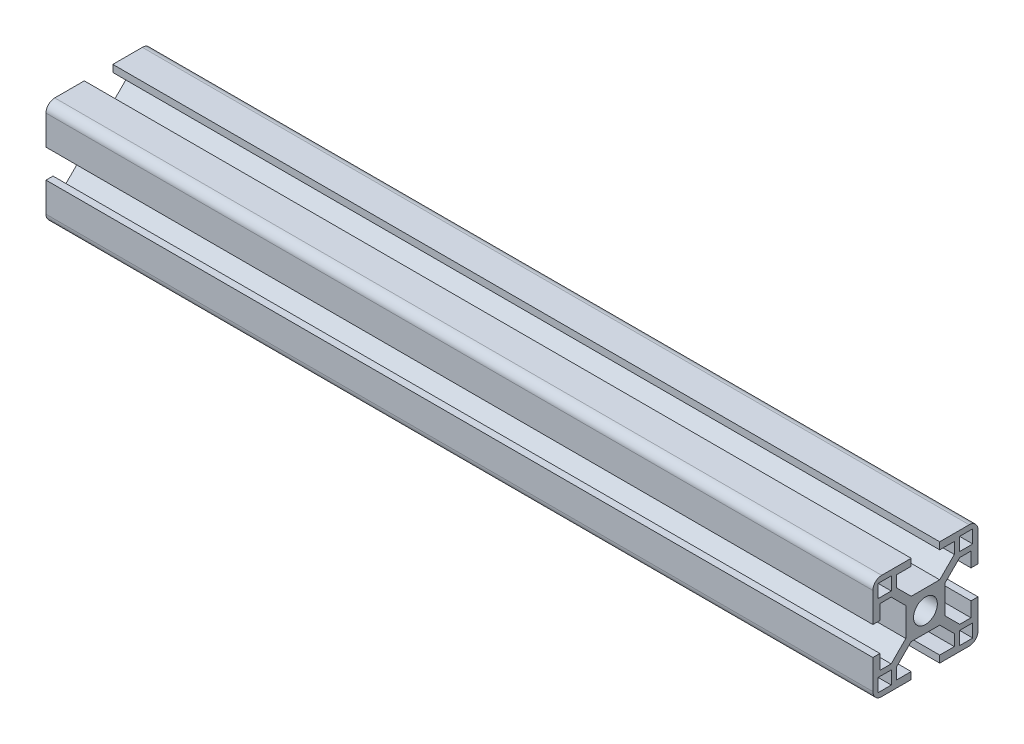
SolidWorks part; units mm, degrees
material "6061 Alloy"
material "6061 Alloy"
ref_plane "Front Plane" through (0, 0, 0) normal (0, 0, 1) x (1, 0, 0)
ref_plane "Top Plane" through (0, 0, 0) normal (0, 1, 0) x (1, 0, 0)
ref_plane "Right Plane" through (0, 0, 0) normal (1, 0, 0) x (0, 0, -1)
sketch "Sketch1" plane through (0, 0, 0) normal (0, 0, 1) x (1, 0, 0)
  line L0 (0, 0) -> (236, 0)
  dimension "D1" = 236
other "T-slot profiles 3030_2(1)"
ref_plane "Plane1" through (0, 0, 0) normal (1, 0, 0) x (0, 1, 0)
sketch "Sketch11" plane through (0, 0, 0) normal (1, 0, 0) x (0, 1, 0)
  line L0 (0, 15) -> (0, -15) construction
  line L1 (-15, -15) -> (15, -15) construction
  line L2 (-15, -15) -> (-15, 15) construction
  line L3 (-15, 15) -> (15, 15) construction
  line L4 (15, -15) -> (15, 15) construction
  line L5 (-15, -15) -> (15, 15) construction
  line L6 (-15, 15) -> (15, -15) construction
  line L7 (-4.07, 5.6) -> (4.07, 5.6)
  line L8 (0, 0) -> (15, 0) construction
  line L9 (-4.07, -5.6) -> (4.07, -5.6)
  line L10 (5.6, -4.07) -> (5.6, 4.07)
  line L11 (-5.6, -4.07) -> (-5.6, 4.07)
  line L12 (-4.07, 5.6) -> (-8.25, 9.78)
  line L13 (4.07, 5.6) -> (8.25, 9.78)
  line L14 (-8.25, 9.78) -> (8.25, 9.78) construction
  line L15 (8.25, 9.78) -> (8.25, 13)
  line L16 (8.25, 13) -> (4.07, 13)
  line L17 (4.07, 13) -> (4.07, 15)
  line L18 (4.07, 15) -> (12.5, 15)
  line L19 (15, 12.5) -> (15, 4.07)
  line L20 (9.78, 8.25) -> (13, 8.25)
  line L21 (13, 8.25) -> (13, 4.07)
  line L22 (9.78, 8.25) -> (5.6, 4.07)
  line L23 (8.25, 9.78) -> (9.78, 8.25) construction
  line L24 (13, 4.07) -> (15, 4.07)
  line L25 (5.6, -4.07) -> (9.78, -8.25)
  line L26 (9.75, 13.5) -> (13.5, 13.5)
  line L27 (9.75, 13.5) -> (9.75, 9.75)
  line L28 (9.75, 9.75) -> (13.5, 9.75)
  line L29 (13.5, 13.5) -> (13.5, 9.75)
  line L30 (9.75, 13.5) -> (13.5, 9.75) construction
  line L31 (9.75, 9.75) -> (13.5, 13.5) construction
  line L32 (9.78, -8.25) -> (13, -8.25)
  line L33 (13, -8.25) -> (13, -4.07)
  line L34 (13, -4.07) -> (15, -4.07)
  line L35 (15, -4.07) -> (15, -12.5)
  line L36 (4.07, -5.6) -> (8.25, -9.78)
  line L37 (8.25, -9.78) -> (8.25, -13)
  line L38 (8.25, -13) -> (4.07, -13)
  line L39 (4.07, -13) -> (4.07, -15)
  line L40 (4.07, -15) -> (12.5, -15)
  line L41 (-4.07, -5.6) -> (-8.25, -9.78)
  line L42 (-8.25, -9.78) -> (-8.25, -13)
  line L43 (-8.25, -13) -> (-4.07, -13)
  line L44 (-4.07, -13) -> (-4.07, -15)
  line L45 (-4.07, -15) -> (-12.5, -15)
  line L46 (-8.25, 9.78) -> (-8.25, 13)
  line L47 (-8.25, 13) -> (-4.07, 13)
  line L48 (-4.07, 13) -> (-4.07, 15)
  line L49 (-4.07, 15) -> (-12.5, 15)
  line L50 (-5.6, 4.07) -> (-9.78, 8.25)
  line L51 (-9.78, 8.25) -> (-13, 8.25)
  line L52 (-13, 8.25) -> (-13, 4.07)
  line L53 (-13, 4.07) -> (-15, 4.07)
  line L54 (-15, 4.07) -> (-15, 12.5)
  line L55 (-5.6, -4.07) -> (-9.78, -8.25)
  line L56 (-9.78, -8.25) -> (-13, -8.25)
  line L57 (-13, -8.25) -> (-13, -4.07)
  line L58 (-13, -4.07) -> (-15, -4.07)
  line L59 (-15, -4.07) -> (-15, -12.5)
  line L60 (9.75, -9.75) -> (13.5, -9.75)
  line L61 (13.5, -13.5) -> (13.5, -9.75)
  line L62 (9.75, -13.5) -> (13.5, -13.5)
  line L63 (9.75, -13.5) -> (9.75, -9.75)
  line L64 (-9.75, 9.75) -> (-13.5, 9.75)
  line L65 (-13.5, 13.5) -> (-13.5, 9.75)
  line L66 (-9.75, 13.5) -> (-13.5, 13.5)
  line L67 (-9.75, 13.5) -> (-9.75, 9.75)
  line L68 (-9.75, -13.5) -> (-9.75, -9.75)
  line L69 (-9.75, -13.5) -> (-13.5, -13.5)
  line L70 (-13.5, -13.5) -> (-13.5, -9.75)
  line L71 (-9.75, -9.75) -> (-13.5, -9.75)
  arc A0 (-15, 12.5) -> (-12.5, 15) centre (-12.5, 12.5) cw
  arc A1 (12.5, -15) -> (15, -12.5) centre (12.5, -12.5) ccw
  arc A2 (15, 12.5) -> (12.5, 15) centre (12.5, 12.5) ccw
  arc A3 (-12.5, -15) -> (-15, -12.5) centre (-12.5, -12.5) cw
  circle A4 centre (0, 0) radius 3.4
  point P0 (0, 0)
  point P6 (0, 0)
  point P7 (-12.5, 12.5)
  point P26 (0, 5.6)
  point P32 (5.6, 0)
  point P44 (11.625, 11.625)
  dimension "D4" = 6.8
  dimension "D3" = 2.5
  dimension "D1" = 30
  dimension "D2" = 30
  dimension "D5" = 8.14
  dimension "D6" = 9.4
  dimension "D7" = 8.14
  dimension "D8" = 9.4
  dimension "D9" = 16.5
  dimension "D10" = 2
  dimension "D11" = 2
  dimension "D12" = 3.75
  dimension "D13" = 3.75
  dimension "D14" = 1.5
  dimension "D15" = 2
  dimension "D16" = 2
  dimension "D17" = 2
  dimension "D18" = 2
  dimension "D19" = 2
  dimension "D20" = 2
